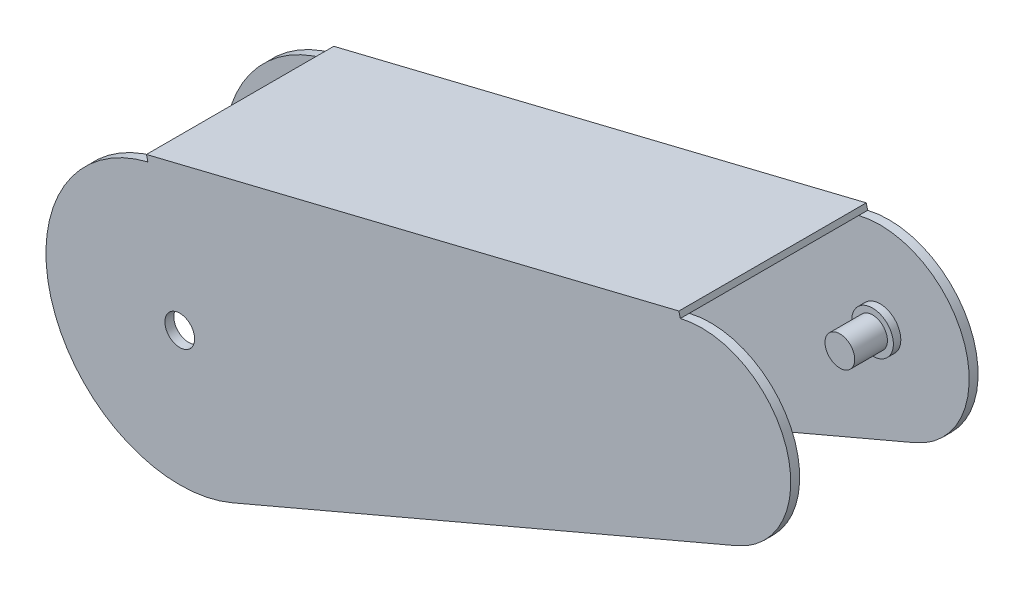
SolidWorks part; units mm, degrees
ref_plane "Front Plane" through (0, 0, 0) normal (0, 0, 1) x (1, 0, 0)
ref_plane "Top Plane" through (0, 0, 0) normal (0, 1, 0) x (1, 0, 0)
ref_plane "Right Plane" through (0, 0, 0) normal (1, 0, 0) x (0, 0, -1)
sketch "Sketch1" plane through (0, 0, 0) normal (0, 0, 1) x (1, 0, 0)
  line L0 (-90.9759, 21.9483) -> (88.1024, 65.8909)
  line L1 (-62.605, -63.1508) -> (107.0163, 9.1582)
  circle A0 centre (-80.2518, -21.7552) radius 5
  circle A1 centre (95.2518, 36.7552) radius 5
  circle A2 centre (-80.2518, -21.7552) radius 45
  circle A3 centre (95.2518, 36.7552) radius 30
extrude "Boss-Extrude1" add sketch "Sketch1" along normal blind 3 contours A3 L0 A2 L1 | A2 A0 | A3 A1
sketch "Sketch2" plane through (-10.2466, 41.7578, 0) normal (-0.2383, 0.9712, 0) x (0.9712, 0.2383, 0)
  line L1 (-83.1242, 0) -> (101.2667, 0)
  line L2 (-83.1242, 0) -> (-83.1242, -63)
  line L3 (-83.1242, -63) -> (101.2667, -63)
  line L4 (101.2667, 0) -> (101.2667, -63)
  dimension "D1" = 63
extrude "Boss-Extrude2" add sketch "Sketch2" along normal blind 2
sketch "Sketch3" plane through (0, 0, 63) normal (0, 0, 1) x (1, 0, 0)
  line L0 (-62.605, -63.1508) -> (107.0163, 9.1582)
  line L1 (-90.9759, 21.9483) -> (88.1024, 65.8909)
  circle A0 centre (-80.2518, -21.7552) radius 5
  circle A1 centre (95.2518, 36.7552) radius 5
  circle A2 centre (95.2518, 36.7552) radius 30
  circle A3 centre (-80.2518, -21.7552) radius 45
  line M1 (-90.9759, 21.9483) -> (88.1024, 65.8909)
extrude "Boss-Extrude3" add sketch "Sketch3" against normal blind 3 contours A3 A0 | A3 L0 A2 M1 | A2 A1
sketch "Sketch5" plane through (0, 0, 3) normal (0, 0, 1) x (1, 0, 0)
  circle A0 centre (95.2518, 36.7552) radius 5
  circle A1 centre (95.2518, 36.7552) radius 7
  dimension "D1" = 14
extrude "Boss-Extrude4" add sketch "Sketch5" along normal blind 2.5
sketch "Sketch7" plane through (0, 0, 60) normal (0, 0, -1) x (-1, 0, 0)
  circle A0 centre (-95.2518, 36.7552) radius 5
  circle A1 centre (-95.2518, 36.7552) radius 7
  dimension "D1" = 14
extrude "Boss-Extrude5" add sketch "Sketch7" along normal blind 2.5
sketch "Sketch8" plane through (0, 0, 63) normal (0, 0, 1) x (1, 0, 0)
  circle A0 centre (95.2518, 36.7552) radius 5
sketch "Sketch11" plane through (0, 0, 57.5) normal (0, 0, -1) x (-1, 0, 0)
  circle A0 centre (-95.2518, 36.7552) radius 5
extrude "Boss-Extrude6" add sketch "Sketch11" against normal up to surface (5.5 mm away) up to face at (2.952, 19.8172, 63)
sketch "Sketch12" plane through (0, 0, 57.5) normal (0, 0, -1) x (-1, 0, 0)
  circle A0 centre (-95.2518, 36.7552) radius 5
  dimension "D1" = 10
extrude "Boss-Extrude7" add sketch "Sketch12" along normal blind 10
sketch "Sketch13" plane through (0, 0, 0) normal (0, 0, -1) x (-1, 0, 0)
  circle A0 centre (-95.2518, 36.7552) radius 5
extrude "Boss-Extrude8" add sketch "Sketch13" against normal blind 16.5
sketch "Sketch14" plane through (0, 0, 57.5) normal (0, 0, -1) x (-1, 0, 0)
  circle A0 centre (-95.2518, 36.7552) radius 5
sketch "Sketch15" plane through (0, 0, 60) normal (0, 0, -1) x (-1, 0, 0)
  line L0 (-95.2518, 36.7552) -> (80.2518, -21.7552)
  line L1 (80.2518, -21.7552) -> (-95.2518, 36.7552)
  line L2 (80.2518, -21.7552) -> (80.5852, -20.7552)
  line L3 (-95.2518, 36.7552) -> (-94.9184, 37.7552)
  line L4 (80.5852, -20.7552) -> (-94.9184, 37.7552)
  circle M6 centre (80.2518, -21.7552) radius 5
  circle M7 centre (-95.2518, 36.7552) radius 7
  dimension "D1" = 1
extrude "Boss-Extrude9" add sketch "Sketch15" along normal blind 5 contours L4 L0 M6 M7
